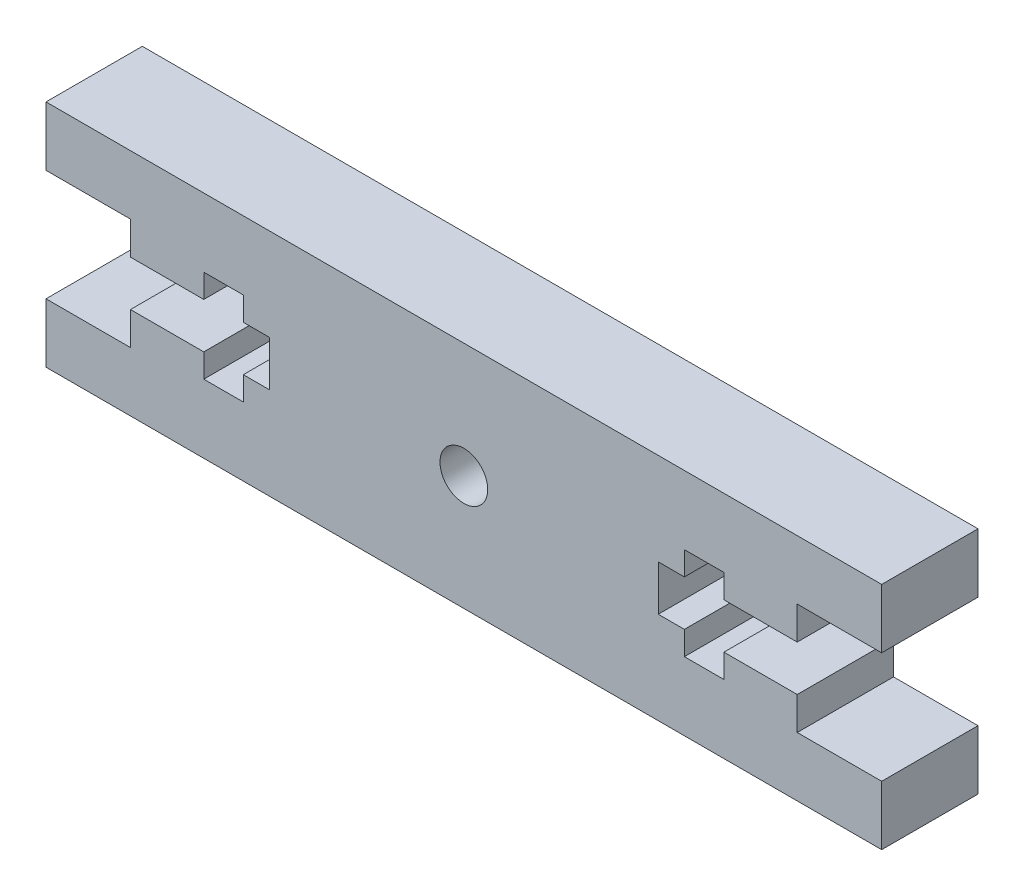
SolidWorks part; units mm, degrees
ref_plane "Front Plane" through (0, 0, 0) normal (0, 0, 1) x (1, 0, 0)
ref_plane "Top Plane" through (0, 0, 0) normal (0, 1, 0) x (1, 0, 0)
ref_plane "Right Plane" through (0, 0, 0) normal (1, 0, 0) x (0, 0, -1)
sketch "Sketch1" plane through (0, 0, 0) normal (0, 0, 1) x (1, 0, 0)
  line L0 (728.3563, 352.6629) -> (779.1165, 352.6629)
  line L1 (753.7364, -654.3154) -> (753.7364, 49345.6846) construction
  line L2 (741.9274, 347.0629) -> (741.9274, 344.3063)
  line L3 (728.3563, 349.0629) -> (733.4864, 349.0629)
  line L4 (733.4864, 349.0629) -> (733.4864, 347.0629)
  line L5 (733.4864, 347.0629) -> (737.9394, 347.0629)
  line L6 (737.9394, 348.5005) -> (740.3401, 348.5005)
  line L7 (-245.8122, 345.6846) -> (49754.1878, 345.6846) construction
  line L8 (728.3563, 338.7063) -> (728.3563, 342.3063)
  line L9 (737.9394, 344.3063) -> (737.9394, 342.8687)
  line L10 (740.3401, 342.8687) -> (740.3401, 344.3063)
  line L11 (740.3401, 344.3063) -> (741.9274, 344.3063)
  line L12 (737.9394, 342.8687) -> (740.3401, 342.8687)
  line L13 (733.4864, 344.3063) -> (737.9394, 344.3063)
  line L14 (740.3401, 347.0629) -> (741.9274, 347.0629)
  line L15 (740.3401, 348.5005) -> (740.3401, 347.0629)
  line L16 (733.4864, 342.3063) -> (733.4864, 344.3063)
  line L17 (737.9394, 347.0629) -> (737.9394, 348.5005)
  line L18 (728.3563, 342.3063) -> (733.4864, 342.3063)
  line L19 (728.3563, 338.7063) -> (779.1165, 338.7063)
  line L20 (779.1165, 352.6629) -> (779.1165, 349.0629)
  line L21 (779.1165, 342.3063) -> (773.9864, 342.3063)
  line L22 (769.5334, 347.0629) -> (769.5334, 348.5005)
  line L23 (773.9864, 342.3063) -> (773.9864, 344.3063)
  line L24 (767.1327, 348.5005) -> (767.1327, 347.0629)
  line L25 (767.1327, 347.0629) -> (765.5454, 347.0629)
  line L26 (773.9864, 344.3063) -> (769.5334, 344.3063)
  line L27 (769.5334, 342.8687) -> (767.1327, 342.8687)
  line L28 (767.1327, 344.3063) -> (765.5454, 344.3063)
  line L29 (767.1327, 342.8687) -> (767.1327, 344.3063)
  line L30 (769.5334, 344.3063) -> (769.5334, 342.8687)
  line L31 (779.1165, 338.7063) -> (779.1165, 342.3063)
  line L32 (769.5334, 348.5005) -> (767.1327, 348.5005)
  line L33 (773.9864, 347.0629) -> (769.5334, 347.0629)
  line L34 (728.3563, 352.6629) -> (728.3563, 349.0629)
  line L35 (773.9864, 349.0629) -> (773.9864, 347.0629)
  line L36 (779.1165, 349.0629) -> (773.9864, 349.0629)
  line L37 (765.5454, 347.0629) -> (765.5454, 344.3063)
  circle A0 centre (753.7364, 345.6846) radius 1.45
  point P7 (753.7364, 352.6629)
  point P8 (765.5454, 345.6846)
  point P24 (741.9274, 345.6846)
  point P28 (753.7364, 338.7063)
  point P46 (753.7364, 352.6629)
  dimension "D1" = 3.6
  dimension "D2" = 4.453
  dimension "D3" = 5.1301
  dimension "D4" = 1.4376
  dimension "D5" = 2.4007
  dimension "D6" = 1.5873
  dimension "D7" = 2
  dimension "D8" = 40.5
  dimension "D9" = 2.7566
extrude "Boss-Extrude2" add sketch "Sketch1" along normal blind 5.85
